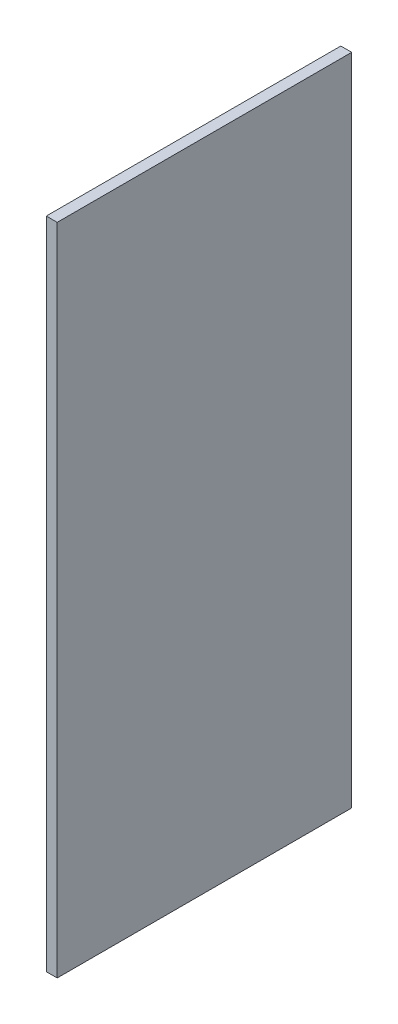
SolidWorks part; units mm, degrees
ref_plane "Front Plane" through (0, 0, 0) normal (0, 0, 1) x (1, 0, 0)
ref_plane "Top Plane" through (0, 0, 0) normal (0, 1, 0) x (1, 0, 0)
ref_plane "Right Plane" through (0, 0, 0) normal (1, 0, 0) x (0, 0, -1)
sketch "Sketch1" plane through (0, 0, 0) normal (1, 0, 0) x (0, 0, -1)
  line L1 (-67.5, -150) -> (67.5, -150)
  line L2 (-67.5, -150) -> (-67.5, 150)
  line L3 (-67.5, 150) -> (67.5, 150)
  line L4 (67.5, -150) -> (67.5, 150)
  line L5 (-67.5, -150) -> (67.5, 150) construction
  line L6 (-67.5, 150) -> (67.5, -150) construction
  point P0 (0, 0)
  dimension "D1" = 300
  dimension "D2" = 135
extrude "Boss-Extrude1" add sketch "Sketch1" along normal blind 5
